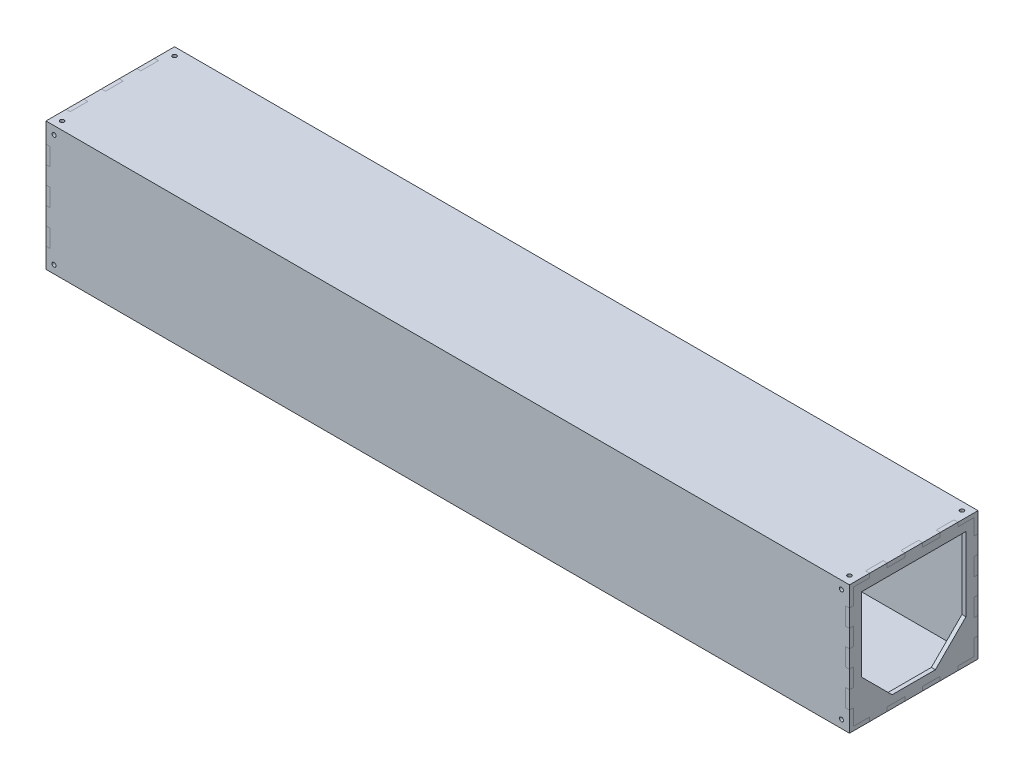
SolidWorks part; units mm, degrees
ref_plane "Front Plane" through (0, 0, 0) normal (0, 0, 1) x (1, 0, 0)
ref_plane "Top Plane" through (0, 0, 0) normal (0, 1, 0) x (1, 0, 0)
ref_plane "Right Plane" through (0, 0, 0) normal (1, 0, 0) x (0, 0, -1)
sketch "Sketch1" plane through (0, 0, 0) normal (1, 0, 0) x (0, 0, -1)
  line L0 (-98.425, 3.175) -> (-98.425, 98.425)
  line L1 (0, 0) -> (-101.6, 0)
  line L2 (0, 0) -> (0, 101.6)
  line L3 (0, 101.6) -> (-101.6, 101.6)
  line L4 (-101.6, 0) -> (-101.6, 101.6)
  line L5 (-3.175, 98.425) -> (-98.425, 98.425)
  line L6 (-3.175, 3.175) -> (-3.175, 98.425)
  line L7 (-3.175, 3.175) -> (-98.425, 3.175)
  dimension "D1" = 101.6
  dimension "D2" = 101.6
  dimension "D3" = 3.175
extrude "Boss-Extrude1" add sketch "Sketch1" along normal blind 628.65
sketch "Sketch3" plane through (0, 0, 0) normal (-1, 0, 0) x (0, 0, 1)
  line L0 (0, 85.725) -> (3.175, 85.725)
  line L1 (0, 0) -> (0, 101.6) construction
  line L2 (3.175, 3.175) -> (3.175, 98.425) construction
  line L3 (15.875, 101.6) -> (15.875, 98.425)
  line L4 (0, 101.6) -> (101.6, 101.6) construction
  line L5 (3.175, 98.425) -> (98.425, 98.425) construction
  line L6 (3.175, 50.8) -> (50.8, 50.8) construction
  line L7 (29.845, 101.6) -> (29.845, 98.425)
  line L8 (43.815, 101.6) -> (43.815, 98.425)
  line L9 (3.175, 98.425) -> (50.8, 50.8) construction
  line L10 (50.8, 50.8) -> (50.8, 98.425) construction
  line L11 (0, 57.785) -> (3.175, 57.785)
  line L12 (0, 71.755) -> (3.175, 71.755)
  line L13 (0, 85.725) -> (0, 101.6)
  line L14 (0, 101.6) -> (15.875, 101.6)
  line L15 (3.175, 85.725) -> (3.175, 98.425)
  line L16 (3.175, 98.425) -> (15.875, 98.425)
  line L17 (29.845, 101.6) -> (43.815, 101.6)
  line L18 (29.845, 98.425) -> (43.815, 98.425)
  line L19 (0, 71.755) -> (0, 57.785)
  line L20 (3.175, 71.755) -> (3.175, 57.785)
  line L21 (98.425, 71.755) -> (98.425, 57.785)
  line L22 (101.6, 71.755) -> (101.6, 57.785)
  line L23 (71.755, 98.425) -> (57.785, 98.425)
  line L24 (71.755, 101.6) -> (57.785, 101.6)
  line L25 (98.425, 98.425) -> (85.725, 98.425)
  line L26 (98.425, 85.725) -> (98.425, 98.425)
  line L27 (101.6, 101.6) -> (85.725, 101.6)
  line L28 (101.6, 85.725) -> (101.6, 101.6)
  line L29 (101.6, 71.755) -> (98.425, 71.755)
  line L30 (101.6, 57.785) -> (98.425, 57.785)
  line L31 (57.785, 101.6) -> (57.785, 98.425)
  line L32 (71.755, 101.6) -> (71.755, 98.425)
  line L33 (85.725, 101.6) -> (85.725, 98.425)
  line L34 (101.6, 85.725) -> (98.425, 85.725)
  line L35 (101.6, 15.875) -> (98.425, 15.875)
  line L36 (85.725, 0) -> (85.725, 3.175)
  line L37 (71.755, 0) -> (71.755, 3.175)
  line L38 (57.785, 0) -> (57.785, 3.175)
  line L39 (101.6, 43.815) -> (98.425, 43.815)
  line L40 (101.6, 29.845) -> (98.425, 29.845)
  line L41 (101.6, 15.875) -> (101.6, 0)
  line L42 (101.6, 0) -> (85.725, 0)
  line L43 (98.425, 15.875) -> (98.425, 3.175)
  line L44 (98.425, 3.175) -> (85.725, 3.175)
  line L45 (71.755, 0) -> (57.785, 0)
  line L46 (71.755, 3.175) -> (57.785, 3.175)
  line L47 (101.6, 29.845) -> (101.6, 43.815)
  line L48 (98.425, 29.845) -> (98.425, 43.815)
  line L49 (3.175, 29.845) -> (3.175, 43.815)
  line L50 (0, 29.845) -> (0, 43.815)
  line L51 (29.845, 3.175) -> (43.815, 3.175)
  line L52 (29.845, 0) -> (43.815, 0)
  line L53 (3.175, 3.175) -> (15.875, 3.175)
  line L54 (3.175, 15.875) -> (3.175, 3.175)
  line L55 (0, 0) -> (15.875, 0)
  line L56 (0, 15.875) -> (0, 0)
  line L57 (0, 29.845) -> (3.175, 29.845)
  line L58 (0, 43.815) -> (3.175, 43.815)
  line L59 (43.815, 0) -> (43.815, 3.175)
  line L60 (29.845, 0) -> (29.845, 3.175)
  line L61 (15.875, 0) -> (15.875, 3.175)
  line L62 (0, 15.875) -> (3.175, 15.875)
  dimension "D1" = 12.7
  dimension "D2" = 12.7
  dimension "D3" = 13.97
  dimension "D4" = 13.97
  dimension "D5" = 45
extrude "Boss-Extrude3" add sketch "Sketch3" along normal blind 3.175
sketch "Sketch4" plane through (0, 0, 0) normal (-1, 0, 0) x (0, 0, 1)
  line L0 (29.845, 98.425) -> (29.845, 101.6) construction
  line L1 (29.845, 101.6) -> (15.875, 101.6) construction
  line L2 (15.875, 101.6) -> (15.875, 98.425) construction
  line L3 (15.875, 98.425) -> (29.845, 98.425) construction
  line L4 (57.785, 98.425) -> (57.785, 101.6) construction
  line L5 (57.785, 101.6) -> (43.815, 101.6) construction
  line L6 (43.815, 101.6) -> (43.815, 98.425) construction
  line L7 (43.815, 98.425) -> (57.785, 98.425) construction
  line L8 (85.725, 98.425) -> (85.725, 101.6) construction
  line L9 (85.725, 101.6) -> (71.755, 101.6) construction
  line L10 (71.755, 101.6) -> (71.755, 98.425) construction
  line L11 (71.755, 98.425) -> (85.725, 98.425) construction
  line L12 (101.6, 85.725) -> (98.425, 85.725) construction
  line L13 (98.425, 85.725) -> (98.425, 71.755) construction
  line L14 (98.425, 71.755) -> (101.6, 71.755) construction
  line L15 (101.6, 71.755) -> (101.6, 85.725) construction
  line L16 (98.425, 43.815) -> (101.6, 43.815) construction
  line L17 (101.6, 43.815) -> (101.6, 57.785) construction
  line L18 (101.6, 57.785) -> (98.425, 57.785) construction
  line L19 (98.425, 57.785) -> (98.425, 43.815) construction
  line L20 (98.425, 15.875) -> (101.6, 15.875) construction
  line L21 (101.6, 15.875) -> (101.6, 29.845) construction
  line L22 (101.6, 29.845) -> (98.425, 29.845) construction
  line L23 (98.425, 29.845) -> (98.425, 15.875) construction
  line L24 (85.725, 0) -> (85.725, 3.175) construction
  line L25 (85.725, 3.175) -> (71.755, 3.175) construction
  line L26 (71.755, 3.175) -> (71.755, 0) construction
  line L27 (71.755, 0) -> (85.725, 0) construction
  line L28 (57.785, 0) -> (57.785, 3.175) construction
  line L29 (57.785, 3.175) -> (43.815, 3.175) construction
  line L30 (43.815, 3.175) -> (43.815, 0) construction
  line L31 (43.815, 0) -> (57.785, 0) construction
  line L32 (15.875, 3.175) -> (15.875, 0) construction
  line L33 (15.875, 0) -> (29.845, 0) construction
  line L34 (29.845, 0) -> (29.845, 3.175) construction
  line L35 (29.845, 3.175) -> (15.875, 3.175) construction
  line L36 (0, 15.875) -> (3.175, 15.875) construction
  line L37 (3.175, 15.875) -> (3.175, 29.845) construction
  line L38 (3.175, 29.845) -> (0, 29.845) construction
  line L39 (0, 29.845) -> (0, 15.875) construction
  line L40 (3.175, 57.785) -> (0, 57.785) construction
  line L41 (0, 57.785) -> (0, 43.815) construction
  line L42 (0, 43.815) -> (3.175, 43.815) construction
  line L43 (3.175, 43.815) -> (3.175, 57.785) construction
  line L44 (0, 71.755) -> (3.175, 71.755) construction
  line L45 (3.175, 71.755) -> (3.175, 85.725) construction
  line L46 (3.175, 85.725) -> (0, 85.725) construction
  line L47 (0, 85.725) -> (0, 71.755) construction
  line L48 (3.175, 57.785) -> (3.175, 71.755) construction
  line L49 (3.175, 29.845) -> (3.175, 43.815) construction
  line L50 (3.175, 3.175) -> (3.175, 15.875) construction
  line L51 (15.875, 3.175) -> (3.175, 3.175) construction
  line L52 (43.815, 3.175) -> (29.845, 3.175) construction
  line L53 (71.755, 3.175) -> (57.785, 3.175) construction
  line L54 (98.425, 3.175) -> (85.725, 3.175) construction
  line L55 (98.425, 15.875) -> (98.425, 3.175) construction
  line L56 (98.425, 43.815) -> (98.425, 29.845) construction
  line L57 (98.425, 71.755) -> (98.425, 57.785) construction
  line L58 (98.425, 98.425) -> (98.425, 85.725) construction
  line L59 (85.725, 98.425) -> (98.425, 98.425) construction
  line L60 (57.785, 98.425) -> (71.755, 98.425) construction
  line L61 (29.845, 98.425) -> (43.815, 98.425) construction
  line L62 (3.175, 98.425) -> (15.875, 98.425) construction
  line L63 (3.175, 85.725) -> (3.175, 98.425) construction
  line L64 (29.845, 98.425) -> (29.845, 101.6)
  line L65 (29.845, 101.6) -> (15.875, 101.6)
  line L66 (15.875, 101.6) -> (15.875, 98.425)
  line L67 (15.875, 98.425) -> (29.845, 98.425)
  line L68 (57.785, 98.425) -> (57.785, 101.6)
  line L69 (57.785, 101.6) -> (43.815, 101.6)
  line L70 (43.815, 101.6) -> (43.815, 98.425)
  line L71 (43.815, 98.425) -> (57.785, 98.425)
  line L72 (85.725, 98.425) -> (85.725, 101.6)
  line L73 (85.725, 101.6) -> (71.755, 101.6)
  line L74 (71.755, 101.6) -> (71.755, 98.425)
  line L75 (71.755, 98.425) -> (85.725, 98.425)
  line L76 (101.6, 85.725) -> (98.425, 85.725)
  line L77 (98.425, 85.725) -> (98.425, 71.755)
  line L78 (98.425, 71.755) -> (101.6, 71.755)
  line L79 (101.6, 71.755) -> (101.6, 85.725)
  line L80 (98.425, 43.815) -> (101.6, 43.815)
  line L81 (101.6, 43.815) -> (101.6, 57.785)
  line L82 (101.6, 57.785) -> (98.425, 57.785)
  line L83 (98.425, 57.785) -> (98.425, 43.815)
  line L84 (98.425, 15.875) -> (101.6, 15.875)
  line L85 (101.6, 15.875) -> (101.6, 29.845)
  line L86 (101.6, 29.845) -> (98.425, 29.845)
  line L87 (98.425, 29.845) -> (98.425, 15.875)
  line L88 (85.725, 0) -> (85.725, 3.175)
  line L89 (85.725, 3.175) -> (71.755, 3.175)
  line L90 (71.755, 3.175) -> (71.755, 0)
  line L91 (71.755, 0) -> (85.725, 0)
  line L92 (57.785, 0) -> (57.785, 3.175)
  line L93 (57.785, 3.175) -> (43.815, 3.175)
  line L94 (43.815, 3.175) -> (43.815, 0)
  line L95 (43.815, 0) -> (57.785, 0)
  line L96 (15.875, 3.175) -> (15.875, 0)
  line L97 (15.875, 0) -> (29.845, 0)
  line L98 (29.845, 0) -> (29.845, 3.175)
  line L99 (29.845, 3.175) -> (15.875, 3.175)
  line L100 (0, 15.875) -> (3.175, 15.875)
  line L101 (3.175, 15.875) -> (3.175, 29.845)
  line L102 (3.175, 29.845) -> (0, 29.845)
  line L103 (0, 29.845) -> (0, 15.875)
  line L104 (3.175, 57.785) -> (0, 57.785)
  line L105 (0, 57.785) -> (0, 43.815)
  line L106 (0, 43.815) -> (3.175, 43.815)
  line L107 (3.175, 43.815) -> (3.175, 57.785)
  line L108 (0, 71.755) -> (3.175, 71.755)
  line L109 (3.175, 71.755) -> (3.175, 85.725)
  line L110 (3.175, 85.725) -> (0, 85.725)
  line L111 (0, 85.725) -> (0, 71.755)
  line L112 (3.175, 57.785) -> (3.175, 71.755)
  line L113 (3.175, 29.845) -> (3.175, 43.815)
  line L114 (3.175, 3.175) -> (3.175, 15.875)
  line L115 (15.875, 3.175) -> (3.175, 3.175)
  line L116 (43.815, 3.175) -> (29.845, 3.175)
  line L117 (71.755, 3.175) -> (57.785, 3.175)
  line L118 (98.425, 3.175) -> (85.725, 3.175)
  line L119 (98.425, 15.875) -> (98.425, 3.175)
  line L120 (98.425, 43.815) -> (98.425, 29.845)
  line L121 (98.425, 71.755) -> (98.425, 57.785)
  line L122 (98.425, 98.425) -> (98.425, 85.725)
  line L123 (85.725, 98.425) -> (98.425, 98.425)
  line L124 (57.785, 98.425) -> (71.755, 98.425)
  line L125 (29.845, 98.425) -> (43.815, 98.425)
  line L126 (3.175, 98.425) -> (15.875, 98.425)
  line L127 (3.175, 85.725) -> (3.175, 98.425)
  line L129 (3.175, 98.425) -> (98.425, 98.425)
  line L130 (3.175, 98.425) -> (3.175, 3.175)
  line L131 (3.175, 3.175) -> (98.425, 3.175)
  line L132 (98.425, 98.425) -> (98.425, 3.175)
  line M5 (0, 71.755) -> (3.175, 71.755)
  line M6 (3.175, 71.755) -> (3.175, 85.725)
  line M7 (3.175, 85.725) -> (0, 85.725)
  line M8 (0, 85.725) -> (0, 71.755)
extrude "Boss-Extrude4" add sketch "Sketch4" along normal blind 3.175 separate body contours L66 L67 L64 L65 | L127 L112 L107 L113 L101 L114 L115 L99 L116 L93 L117 L89 L118 L119 L87 L120 L83 L121 L77 L122 L123 L75 L124 L71 L125 L67 L126 M6 | L70 L71 L68 L69 | L74 L75 L72 L73 | L78 L79 L76 L77 | L82 L83 L80 L81 | L86 L87 L84 L85 | L90 L91 L88 L89 | L94 L95 L92 L93 | L98 L99 L96 L97 | L102 L103 L100 L101 | L106 L107 L104 L105 | M8 M5 M6 M7
sketch "Sketch5" plane through (628.65, 0, 0) normal (1, 0, 0) x (0, 0, -1)
  line L0 (-92.075, 33.7033) -> (-67.8967, 9.525)
  line L1 (-92.075, 92.075) -> (-9.525, 92.075)
  line L2 (-92.075, 92.075) -> (-92.075, 9.525) construction
  line L3 (-92.075, 9.525) -> (-9.525, 9.525) construction
  line L4 (-9.525, 92.075) -> (-9.525, 9.525) construction
  line L5 (-33.7033, 9.525) -> (-9.525, 33.7033)
  line L6 (-67.8967, 9.525) -> (-33.7033, 9.525)
  line L7 (-92.075, 33.7033) -> (-92.075, 92.075)
  line L8 (-9.525, 92.075) -> (-9.525, 33.7033)
  line L52 (-15.875, 98.425) -> (-15.875, 101.6)
  line L53 (-3.175, 98.425) -> (-15.875, 98.425)
  line L54 (-3.175, 85.725) -> (-3.175, 98.425)
  line L55 (0, 85.725) -> (-3.175, 85.725)
  line L56 (0, 71.755) -> (0, 85.725)
  line L57 (-3.175, 71.755) -> (0, 71.755)
  line L58 (-3.175, 57.785) -> (-3.175, 71.755)
  line L59 (0, 57.785) -> (-3.175, 57.785)
  line L60 (0, 43.815) -> (0, 57.785)
  line L61 (-3.175, 43.815) -> (0, 43.815)
  line L62 (-3.175, 29.845) -> (-3.175, 43.815)
  line L63 (0, 29.845) -> (-3.175, 29.845)
  line L64 (0, 15.875) -> (0, 29.845)
  line L65 (-3.175, 15.875) -> (0, 15.875)
  line L66 (-3.175, 3.175) -> (-3.175, 15.875)
  line L67 (-15.875, 3.175) -> (-3.175, 3.175)
  line L68 (-15.875, 0) -> (-15.875, 3.175)
  line L69 (-29.845, 0) -> (-15.875, 0)
  line L70 (-29.845, 3.175) -> (-29.845, 0)
  line L71 (-43.815, 3.175) -> (-29.845, 3.175)
  line L72 (-43.815, 0) -> (-43.815, 3.175)
  line L73 (-57.785, 0) -> (-43.815, 0)
  line L74 (-57.785, 3.175) -> (-57.785, 0)
  line L75 (-71.755, 3.175) -> (-57.785, 3.175)
  line L76 (-71.755, 0) -> (-71.755, 3.175)
  line L77 (-85.725, 0) -> (-71.755, 0)
  line L78 (-85.725, 3.175) -> (-85.725, 0)
  line L79 (-98.425, 3.175) -> (-85.725, 3.175)
  line L80 (-98.425, 15.875) -> (-98.425, 3.175)
  line L81 (-101.6, 15.875) -> (-98.425, 15.875)
  line L82 (-101.6, 29.845) -> (-101.6, 15.875)
  line L83 (-98.425, 29.845) -> (-101.6, 29.845)
  line L84 (-98.425, 43.815) -> (-98.425, 29.845)
  line L85 (-101.6, 43.815) -> (-98.425, 43.815)
  line L86 (-101.6, 57.785) -> (-101.6, 43.815)
  line L87 (-98.425, 57.785) -> (-101.6, 57.785)
  line L88 (-98.425, 71.755) -> (-98.425, 57.785)
  line L89 (-101.6, 71.755) -> (-98.425, 71.755)
  line L90 (-101.6, 85.725) -> (-101.6, 71.755)
  line L91 (-98.425, 85.725) -> (-101.6, 85.725)
  line L92 (-98.425, 98.425) -> (-98.425, 85.725)
  line L93 (-85.725, 98.425) -> (-98.425, 98.425)
  line L94 (-85.725, 101.6) -> (-85.725, 98.425)
  line L95 (-71.755, 101.6) -> (-85.725, 101.6)
  line L96 (-71.755, 98.425) -> (-71.755, 101.6)
  line L97 (-57.785, 98.425) -> (-71.755, 98.425)
  line L98 (-57.785, 101.6) -> (-57.785, 98.425)
  line L99 (-43.815, 101.6) -> (-57.785, 101.6)
  line L100 (-43.815, 98.425) -> (-43.815, 101.6)
  line L101 (-29.845, 98.425) -> (-43.815, 98.425)
  line L102 (-29.845, 101.6) -> (-29.845, 98.425)
  line L103 (-15.875, 101.6) -> (-29.845, 101.6)
  line L104 (-15.875, 98.425) -> (-15.875, 101.6)
  line L105 (-3.175, 98.425) -> (-15.875, 98.425)
  line L106 (-3.175, 85.725) -> (-3.175, 98.425)
  line L107 (0, 85.725) -> (-3.175, 85.725)
  line L108 (0, 71.755) -> (0, 85.725)
  line L109 (-3.175, 71.755) -> (0, 71.755)
  line L110 (-3.175, 57.785) -> (-3.175, 71.755)
  line L111 (0, 57.785) -> (-3.175, 57.785)
  line L112 (0, 43.815) -> (0, 57.785)
  line L113 (-3.175, 43.815) -> (0, 43.815)
  line L114 (-3.175, 29.845) -> (-3.175, 43.815)
  line L115 (0, 29.845) -> (-3.175, 29.845)
  line L116 (0, 15.875) -> (0, 29.845)
  line L117 (-3.175, 15.875) -> (0, 15.875)
  line L118 (-3.175, 3.175) -> (-3.175, 15.875)
  line L119 (-15.875, 3.175) -> (-3.175, 3.175)
  line L120 (-15.875, 0) -> (-15.875, 3.175)
  line L121 (-29.845, 0) -> (-15.875, 0)
  line L122 (-29.845, 3.175) -> (-29.845, 0)
  line L123 (-43.815, 3.175) -> (-29.845, 3.175)
  line L124 (-43.815, 0) -> (-43.815, 3.175)
  line L125 (-57.785, 0) -> (-43.815, 0)
  line L126 (-57.785, 3.175) -> (-57.785, 0)
  line L127 (-71.755, 3.175) -> (-57.785, 3.175)
  line L128 (-71.755, 0) -> (-71.755, 3.175)
  line L129 (-85.725, 0) -> (-71.755, 0)
  line L130 (-85.725, 3.175) -> (-85.725, 0)
  line L131 (-98.425, 3.175) -> (-85.725, 3.175)
  line L132 (-98.425, 15.875) -> (-98.425, 3.175)
  line L133 (-101.6, 15.875) -> (-98.425, 15.875)
  line L134 (-101.6, 29.845) -> (-101.6, 15.875)
  line L135 (-98.425, 29.845) -> (-101.6, 29.845)
  line L136 (-98.425, 43.815) -> (-98.425, 29.845)
  line L137 (-101.6, 43.815) -> (-98.425, 43.815)
  line L138 (-101.6, 57.785) -> (-101.6, 43.815)
  line L139 (-98.425, 57.785) -> (-101.6, 57.785)
  line L140 (-98.425, 71.755) -> (-98.425, 57.785)
  line L141 (-101.6, 71.755) -> (-98.425, 71.755)
  line L142 (-101.6, 85.725) -> (-101.6, 71.755)
  line L143 (-98.425, 85.725) -> (-101.6, 85.725)
  line L144 (-98.425, 98.425) -> (-98.425, 85.725)
  line L145 (-85.725, 98.425) -> (-98.425, 98.425)
  line L146 (-85.725, 101.6) -> (-85.725, 98.425)
  line L147 (-71.755, 101.6) -> (-85.725, 101.6)
  line L148 (-71.755, 98.425) -> (-71.755, 101.6)
  line L149 (-57.785, 98.425) -> (-71.755, 98.425)
  line L150 (-57.785, 101.6) -> (-57.785, 98.425)
  line L151 (-43.815, 101.6) -> (-57.785, 101.6)
  line L152 (-43.815, 98.425) -> (-43.815, 101.6)
  line L153 (-29.845, 98.425) -> (-43.815, 98.425)
  line L154 (-29.845, 101.6) -> (-29.845, 98.425)
  line L155 (-15.875, 101.6) -> (-29.845, 101.6)
  circle A0 centre (-50.8, 50.8) radius 41.275
  line M56 (0, 0) -> (0, 101.6)
  line M57 (0, 101.6) -> (-101.6, 101.6)
  line M58 (-101.6, 101.6) -> (-101.6, 0)
  line M59 (-101.6, 0) -> (0, 0)
  line M60 (-3.175, 98.425) -> (-3.175, 3.175)
  line M61 (-3.175, 3.175) -> (-98.425, 3.175)
  line M62 (-98.425, 3.175) -> (-98.425, 98.425)
  line M63 (-98.425, 98.425) -> (-3.175, 98.425)
  dimension "D2" = 82.55
  dimension "D3" = 82.55
  dimension "D4" = 6.35
  dimension "D5" = 6.35
  dimension "D6" = 45
  dimension "D7" = 45
  dimension "D1" = 0
extrude "Boss-Extrude5" add sketch "Sketch5" along normal blind 3.175 separate body contours L1 L8 L5 L6 L0 L7 M60 M63 M62 M61 | L135 L133 M62 M58 | L139 L137 M62 M58 | L143 L141 M62 M58 | L148 L146 M63 M57 | L152 L150 M63 M57 | L154 L104 M57 M63 | L109 L107 M60 M56 | L113 L111 M60 M56 | L117 L115 M60 M56 | L122 L120 M61 M59 | L126 L124 M61 M59 | L130 L128 M61 M59
sketch "Sketch6" plane through (628.65, 0, 0) normal (1, 0, 0) x (0, 0, -1)
  line L0 (-101.6, 29.845) -> (-101.6, 43.815) construction
  line L1 (-101.6, 43.815) -> (-98.425, 43.815) construction
  line L2 (-98.425, 43.815) -> (-98.425, 29.845) construction
  line L3 (-98.425, 29.845) -> (-101.6, 29.845) construction
  line L4 (-101.6, 71.755) -> (-98.425, 71.755) construction
  line L5 (-98.425, 71.755) -> (-98.425, 57.785) construction
  line L6 (-98.425, 57.785) -> (-101.6, 57.785) construction
  line L7 (-101.6, 57.785) -> (-101.6, 71.755) construction
  line L8 (-98.425, 98.425) -> (-98.425, 85.725) construction
  line L9 (-98.425, 85.725) -> (-101.6, 85.725) construction
  line L10 (-101.6, 85.725) -> (-101.6, 101.6) construction
  line L11 (-101.6, 101.6) -> (-85.725, 101.6) construction
  line L12 (-85.725, 101.6) -> (-85.725, 98.425) construction
  line L13 (-85.725, 98.425) -> (-98.425, 98.425) construction
  line L14 (-71.755, 98.425) -> (-71.755, 101.6) construction
  line L15 (-71.755, 101.6) -> (-57.785, 101.6) construction
  line L16 (-57.785, 101.6) -> (-57.785, 98.425) construction
  line L17 (-57.785, 98.425) -> (-71.755, 98.425) construction
  line L18 (-43.815, 101.6) -> (-29.845, 101.6) construction
  line L19 (-29.845, 101.6) -> (-29.845, 98.425) construction
  line L20 (-29.845, 98.425) -> (-43.815, 98.425) construction
  line L21 (-43.815, 98.425) -> (-43.815, 101.6) construction
  line L22 (0, 101.6) -> (0, 85.725) construction
  line L23 (0, 85.725) -> (-3.175, 85.725) construction
  line L24 (-3.175, 85.725) -> (-3.175, 98.425) construction
  line L25 (-3.175, 98.425) -> (-15.875, 98.425) construction
  line L26 (-15.875, 98.425) -> (-15.875, 101.6) construction
  line L27 (-15.875, 101.6) -> (0, 101.6) construction
  line L28 (0, 71.755) -> (0, 57.785) construction
  line L29 (0, 57.785) -> (-3.175, 57.785) construction
  line L30 (-3.175, 57.785) -> (-3.175, 71.755) construction
  line L31 (-3.175, 71.755) -> (0, 71.755) construction
  line L32 (0, 29.845) -> (-3.175, 29.845) construction
  line L33 (-3.175, 29.845) -> (-3.175, 43.815) construction
  line L34 (-3.175, 43.815) -> (0, 43.815) construction
  line L35 (0, 43.815) -> (0, 29.845) construction
  line L36 (-3.175, 3.175) -> (-3.175, 15.875) construction
  line L37 (-3.175, 15.875) -> (0, 15.875) construction
  line L38 (0, 15.875) -> (0, 0) construction
  line L39 (0, 0) -> (-15.875, 0) construction
  line L40 (-15.875, 0) -> (-15.875, 3.175) construction
  line L41 (-15.875, 3.175) -> (-3.175, 3.175) construction
  line L42 (-29.845, 3.175) -> (-29.845, 0) construction
  line L43 (-29.845, 0) -> (-43.815, 0) construction
  line L44 (-43.815, 0) -> (-43.815, 3.175) construction
  line L45 (-43.815, 3.175) -> (-29.845, 3.175) construction
  line L46 (-57.785, 0) -> (-71.755, 0) construction
  line L47 (-71.755, 0) -> (-71.755, 3.175) construction
  line L48 (-71.755, 3.175) -> (-57.785, 3.175) construction
  line L49 (-57.785, 3.175) -> (-57.785, 0) construction
  line L50 (-101.6, 0) -> (-101.6, 15.875) construction
  line L51 (-101.6, 15.875) -> (-98.425, 15.875) construction
  line L52 (-98.425, 15.875) -> (-98.425, 3.175) construction
  line L53 (-98.425, 3.175) -> (-85.725, 3.175) construction
  line L54 (-85.725, 3.175) -> (-85.725, 0) construction
  line L55 (-85.725, 0) -> (-101.6, 0) construction
  line L56 (-101.6, 29.845) -> (-101.6, 43.815)
  line L57 (-101.6, 43.815) -> (-98.425, 43.815)
  line L58 (-98.425, 43.815) -> (-98.425, 29.845)
  line L59 (-98.425, 29.845) -> (-101.6, 29.845)
  line L60 (-101.6, 71.755) -> (-98.425, 71.755)
  line L61 (-98.425, 71.755) -> (-98.425, 57.785)
  line L62 (-98.425, 57.785) -> (-101.6, 57.785)
  line L63 (-101.6, 57.785) -> (-101.6, 71.755)
  line L64 (-98.425, 98.425) -> (-98.425, 85.725)
  line L65 (-98.425, 85.725) -> (-101.6, 85.725)
  line L66 (-101.6, 85.725) -> (-101.6, 101.6)
  line L67 (-101.6, 101.6) -> (-85.725, 101.6)
  line L68 (-85.725, 101.6) -> (-85.725, 98.425)
  line L69 (-85.725, 98.425) -> (-98.425, 98.425)
  line L70 (-71.755, 98.425) -> (-71.755, 101.6)
  line L71 (-71.755, 101.6) -> (-57.785, 101.6)
  line L72 (-57.785, 101.6) -> (-57.785, 98.425)
  line L73 (-57.785, 98.425) -> (-71.755, 98.425)
  line L74 (-43.815, 101.6) -> (-29.845, 101.6)
  line L75 (-29.845, 101.6) -> (-29.845, 98.425)
  line L76 (-29.845, 98.425) -> (-43.815, 98.425)
  line L77 (-43.815, 98.425) -> (-43.815, 101.6)
  line L78 (0, 101.6) -> (0, 85.725)
  line L79 (0, 85.725) -> (-3.175, 85.725)
  line L80 (-3.175, 85.725) -> (-3.175, 98.425)
  line L81 (-3.175, 98.425) -> (-15.875, 98.425)
  line L82 (-15.875, 98.425) -> (-15.875, 101.6)
  line L83 (-15.875, 101.6) -> (0, 101.6)
  line L84 (0, 71.755) -> (0, 57.785)
  line L85 (0, 57.785) -> (-3.175, 57.785)
  line L86 (-3.175, 57.785) -> (-3.175, 71.755)
  line L87 (-3.175, 71.755) -> (0, 71.755)
  line L88 (0, 29.845) -> (-3.175, 29.845)
  line L89 (-3.175, 29.845) -> (-3.175, 43.815)
  line L90 (-3.175, 43.815) -> (0, 43.815)
  line L91 (0, 43.815) -> (0, 29.845)
  line L92 (-3.175, 3.175) -> (-3.175, 15.875)
  line L93 (-3.175, 15.875) -> (0, 15.875)
  line L94 (0, 15.875) -> (0, 0)
  line L95 (0, 0) -> (-15.875, 0)
  line L96 (-15.875, 0) -> (-15.875, 3.175)
  line L97 (-15.875, 3.175) -> (-3.175, 3.175)
  line L98 (-29.845, 3.175) -> (-29.845, 0)
  line L99 (-29.845, 0) -> (-43.815, 0)
  line L100 (-43.815, 0) -> (-43.815, 3.175)
  line L101 (-43.815, 3.175) -> (-29.845, 3.175)
  line L102 (-57.785, 0) -> (-71.755, 0)
  line L103 (-71.755, 0) -> (-71.755, 3.175)
  line L104 (-71.755, 3.175) -> (-57.785, 3.175)
  line L105 (-57.785, 3.175) -> (-57.785, 0)
  line L106 (-101.6, 0) -> (-101.6, 15.875)
  line L107 (-101.6, 15.875) -> (-98.425, 15.875)
  line L108 (-98.425, 15.875) -> (-98.425, 3.175)
  line L109 (-98.425, 3.175) -> (-85.725, 3.175)
  line L110 (-85.725, 3.175) -> (-85.725, 0)
  line L111 (-85.725, 0) -> (-101.6, 0)
extrude "Boss-Extrude6" add sketch "Sketch6" along normal blind 3.175
sketch "Sketch7" plane through (0, 0, 0) normal (0, 0, -1) x (-1, 0, 0)
  line L0 (-628.65, 50.8) -> (-593.7859, 50.8)
  line L1 (-628.65, 43.815) -> (-628.65, 57.785) construction
  line L2 (-314.325, 101.6) -> (-314.325, 65.2781)
  line L3 (-631.825, 101.6) -> (3.175, 101.6) construction
  line L4 (-631.825, 85.725) -> (-631.825, 101.6) construction
  circle A0 centre (-625.475, 95.25) radius 1.5875
  circle A1 centre (-625.475, 6.35) radius 1.5875
  circle A2 centre (-3.175, 6.35) radius 1.5875
  circle A3 centre (-3.175, 95.25) radius 1.5875
  dimension "D1" = 3.175
  dimension "D2" = 6.35
  dimension "D3" = 6.35
extrude "Cut-Extrude1" cut sketch "Sketch7" against normal through all contours A0 | A1 | A3 | A2
sketch "Sketch8" plane through (0, 101.6, 0) normal (0, 1, 0) x (1, 0, 0)
  line L0 (631.825, 0) -> (-3.175, 0) construction
  line L1 (-3.175, -15.875) -> (-3.175, 0) construction
  line L2 (0, -50.8) -> (30.0165, -50.8)
  line L3 (0, -43.815) -> (0, -57.785) construction
  line L4 (314.325, 0) -> (314.325, -27.8872)
  circle A0 centre (3.175, -6.35) radius 1.5875
  circle A1 centre (3.175, -95.25) radius 1.5875
  circle A2 centre (625.475, -95.25) radius 1.5875
  circle A3 centre (625.475, -6.35) radius 1.5875
  dimension "D1" = 3.175
  dimension "D2" = 6.35
  dimension "D3" = 6.35
extrude "Cut-Extrude2" cut sketch "Sketch8" against normal through all contours A0 | A3 | A2 | A1
